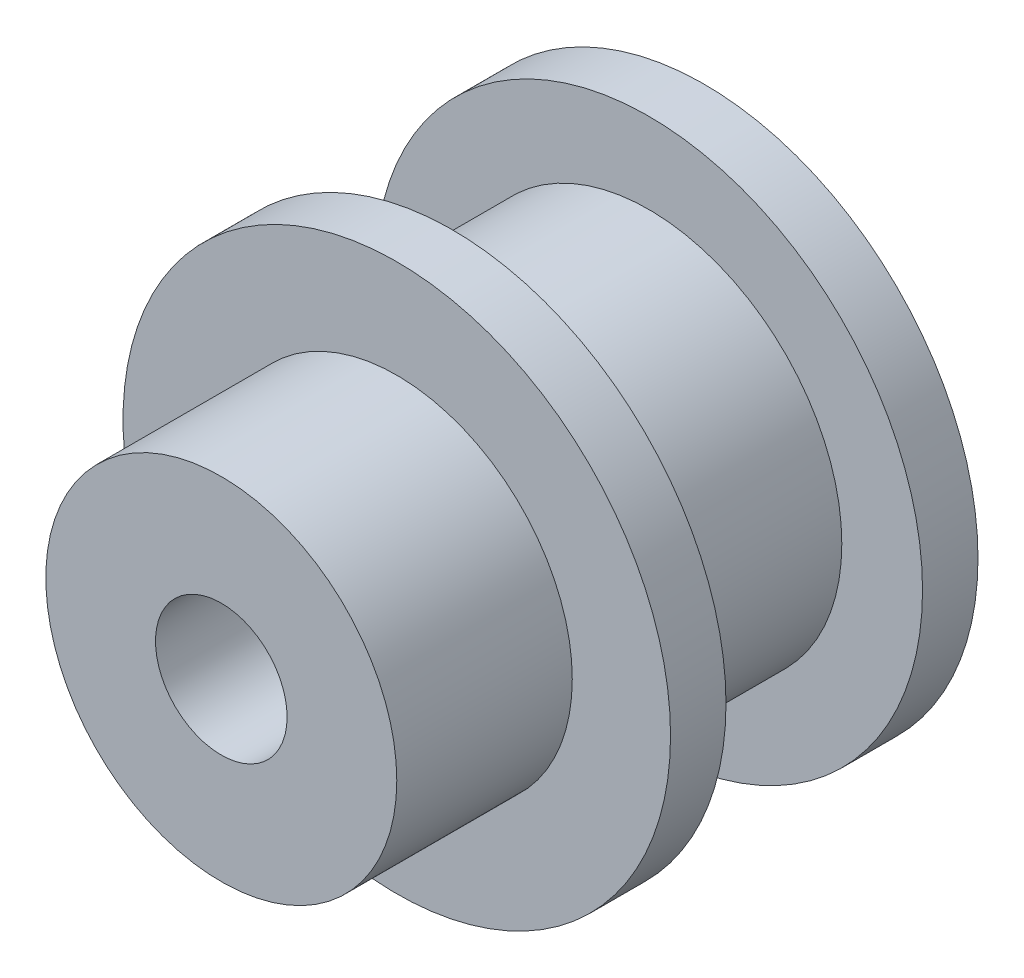
SolidWorks part; units mm, degrees
ref_plane "Front Plane" through (0, 0, 0) normal (0, 0, 1) x (1, 0, 0)
ref_plane "Top Plane" through (0, 0, 0) normal (0, 1, 0) x (1, 0, 0)
ref_plane "Right Plane" through (0, 0, 0) normal (1, 0, 0) x (0, 0, -1)
sketch "Sketch1" plane through (0, 0, 0) normal (1, 0, 0) x (0, 0, -1)
  line L0 (0, 0) -> (13243.007, 0) construction
  line L1 (0, 2.3813) -> (17.4752, 2.3813)
  line L2 (17.4752, 2.3813) -> (17.4752, 9.906)
  line L3 (17.4752, 9.906) -> (15.4686, 9.906)
  line L4 (15.4686, 9.906) -> (15.4686, 6.985)
  line L5 (15.4686, 6.985) -> (8.3566, 6.985)
  line L6 (8.3566, 6.985) -> (8.3566, 9.906)
  line L7 (8.3566, 9.906) -> (6.35, 9.906)
  line L8 (6.35, 9.906) -> (6.35, 6.35)
  line L9 (6.35, 6.35) -> (0, 6.35)
  line L10 (0, 6.35) -> (0, 2.3813)
  dimension "D1" = 4.7625
  dimension "D2" = 12.7
  dimension "D3" = 19.812
  dimension "D4" = 13.97
  dimension "D5" = 7.112
  dimension "D6" = 17.4752
  dimension "D7" = 11.1252
revolve "Revolve1" add sketch "Sketch1" angle 360 about L0
